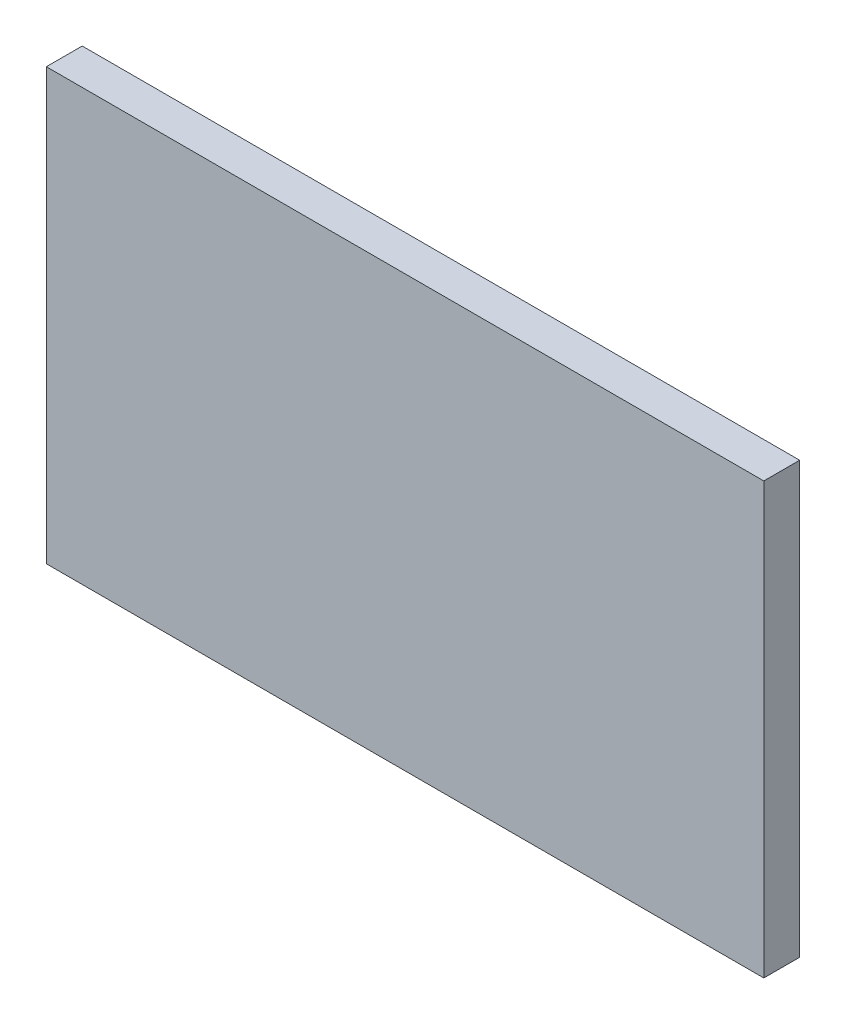
SolidWorks part; units mm, degrees
ref_plane "Front Plane" through (0, 0, 0) normal (0, 0, 1) x (1, 0, 0)
ref_plane "Top Plane" through (0, 0, 0) normal (0, 1, 0) x (1, 0, 0)
ref_plane "Right Plane" through (0, 0, 0) normal (1, 0, 0) x (0, 0, -1)
sketch "Sketch1" plane through (0, 0, 0) normal (0, 1, 0) x (1, 0, 0)
  line L1 (-7.5, 0.25) -> (7.5, 0.25)
  line L2 (-7.5, 0.25) -> (-7.5, -0.5)
  line L3 (-7.5, -0.5) -> (7.5, -0.5)
  line L4 (7.5, 0.25) -> (7.5, -0.5)
  dimension "D1" = 15
  dimension "D2" = 0.75
  dimension "D3" = 0.5
  dimension "D4" = 7.5
extrude "Boss-Extrude1" add sketch "Sketch1" along normal blind 9
